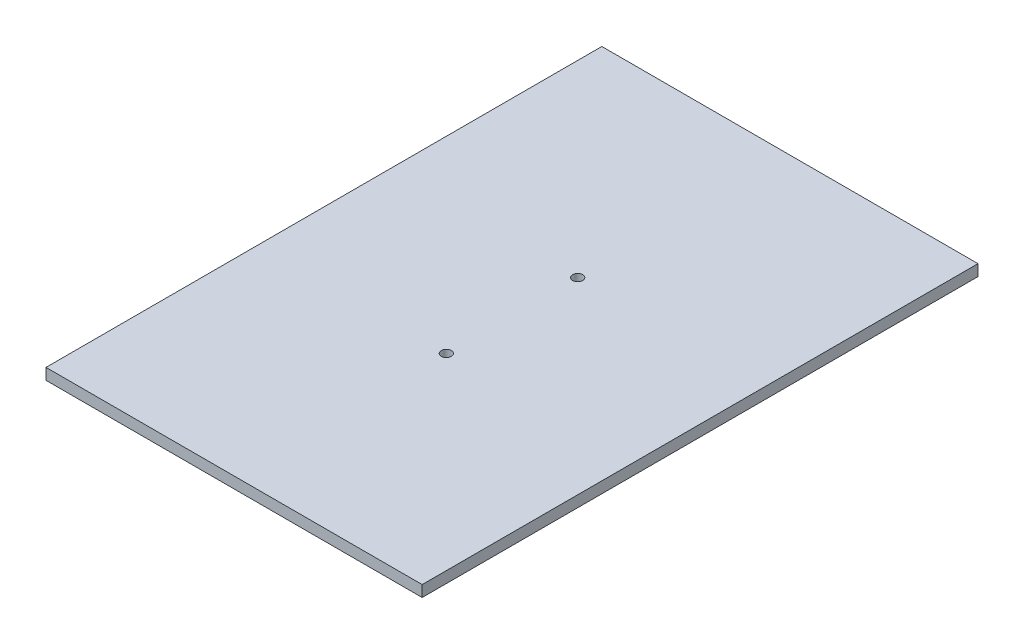
SolidWorks part; units mm, degrees
material "Makrolon"
ref_plane "Vorne" through (0, 0, 0) normal (0, 0, 1) x (1, 0, 0)
ref_plane "Oben" through (0, 0, 0) normal (0, 1, 0) x (1, 0, 0)
ref_plane "Rechts" through (0, 0, 0) normal (1, 0, 0) x (0, 0, -1)
sketch "Skizze1" plane through (0, 0, 0) normal (0, 0, 1) x (1, 0, 0)
  line L1 (-167.5, 5) -> (167.5, 5)
  line L2 (-167.5, 5) -> (-167.5, -5)
  line L3 (-167.5, -5) -> (167.5, -5)
  line L4 (167.5, 5) -> (167.5, -5)
  line L5 (-167.5, 5) -> (167.5, -5) construction
  line L6 (-167.5, -5) -> (167.5, 5) construction
  point P0 (0, 0)
  dimension "D1" = 335
  dimension "D2" = 10
extrude "Aufsatz-Linear austragen1" add sketch "Skizze1" along normal mid plane 495
hole_wizard "Durchgangsloch für M81" positions "Skizze3" profile "Skizze2" hole size "M8" standard "Gabler-Normteile" end condition through all
sketch "Skizze3" plane through (0, 5, 0) normal (0, 1, 0) x (1, 0, 0)
  line L0 (0, 58.5) -> (0, -58.5) construction
  point P0 (0, 58.5)
  point P2 (0, -58.5)
  point P9 (0, 0)
  dimension "D1" = 117
sketch "Skizze2" plane through (0, 5, -58.5) normal (1, 0, 0) x (0, 0, 1)
  line L0 (0, 0) -> (0, 10)
  line L1 (0, 10) -> (4.5, 10)
  line L2 (4.5, 10) -> (4.5, 0)
  line L5 (4.5, 0) -> (0, 0)
  line L11 (0, -6.35) -> (0, 107.95) construction
  dimension "Bohrerdurchmesser" = 9
  dimension "Bohrungstiefe" = 10
